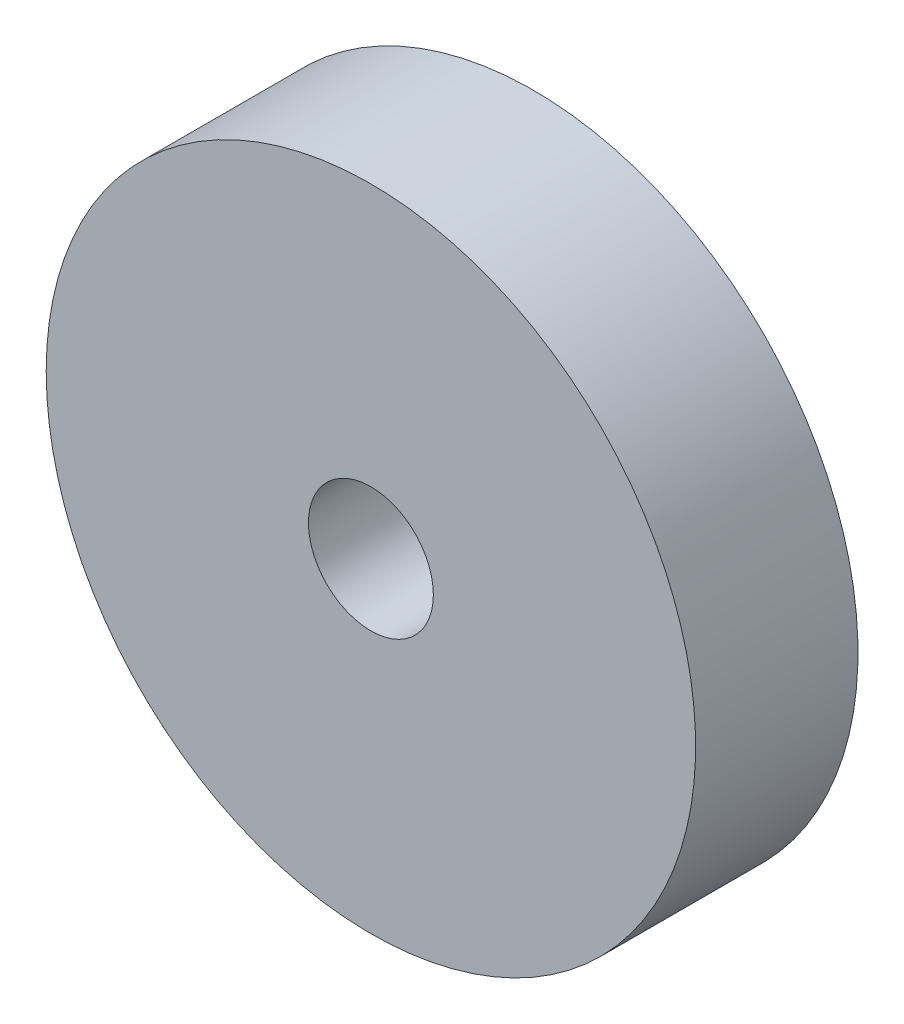
SolidWorks part; units mm, degrees
ref_plane "Front Plane" through (0, 0, 0) normal (0, 0, 1) x (1, 0, 0)
ref_plane "Top Plane" through (0, 0, 0) normal (0, 1, 0) x (1, 0, 0)
ref_plane "Right Plane" through (0, 0, 0) normal (1, 0, 0) x (0, 0, -1)
sketch "Sketch1" plane through (0, 0, 0) normal (0, 0, 1) x (1, 0, 0)
  circle A0 centre (0, 0) radius 13
  dimension "D1" = 26
extrude "Boss-Extrude1" add sketch "Sketch1" along normal blind 6.5
sketch "Sketch2" plane through (0, 0, 6.5) normal (0, 0, 1) x (1, 0, 0)
  circle A0 centre (0, 0) radius 2.5
  dimension "D1" = 5
extrude "Cut-Extrude1" cut sketch "Sketch2" against normal up to next
